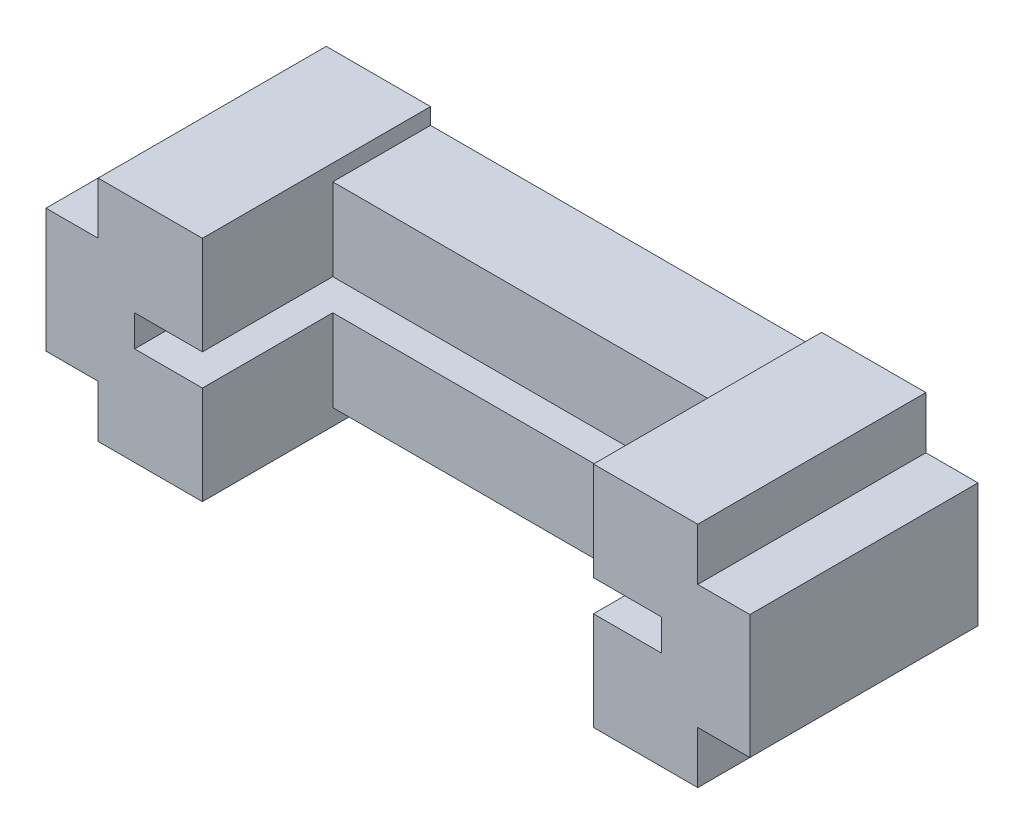
SolidWorks part; units mm, degrees
ref_plane "Front Plane" through (0, 0, 0) normal (0, 0, 1) x (1, 0, 0)
ref_plane "Top Plane" through (0, 0, 0) normal (0, 1, 0) x (1, 0, 0)
ref_plane "Right Plane" through (0, 0, 0) normal (1, 0, 0) x (0, 0, -1)
sketch "Sketch1" plane through (0, 0, 0) normal (0, 0, 1) x (1, 0, 0)
  line L1 (-29.21, -11.1125) -> (29.21, -11.1125)
  line L2 (-34.29, -6.0325) -> (-34.29, 6.0325)
  line L3 (-29.21, 11.1125) -> (29.21, 11.1125)
  line L4 (34.29, -6.0325) -> (34.29, 6.0325)
  line L9 (-34.29, 6.0325) -> (-29.21, 6.0325)
  line L10 (-29.21, 11.1125) -> (-29.21, 6.0325)
  line L13 (-34.29, -6.0325) -> (-29.21, -6.0325)
  line L14 (-29.21, -11.1125) -> (-29.21, -6.0325)
  line L17 (34.29, -6.0325) -> (29.21, -6.0325)
  line L18 (29.21, -11.1125) -> (29.21, -6.0325)
  line L21 (34.29, 6.0325) -> (29.21, 6.0325)
  line L22 (29.21, 11.1125) -> (29.21, 6.0325)
  point P0 (0, 0)
  point P2 (0, 11.1125)
  point P4 (-34.29, 0)
  dimension "D1" = 68.58
  dimension "D2" = 22.225
  dimension "D3" = 5.08
extrude "Boss-Extrude1" add sketch "Sketch1" along normal blind 9.525
sketch "Sketch3" plane through (0, 0, 9.525) normal (0, 0, 1) x (1, 0, 0)
  line L0 (29.21, 11.1125) -> (-29.21, 11.1125) construction
  line L1 (-29.21, 11.1125) -> (-19.05, 11.1125)
  line L2 (-34.29, 6.0325) -> (-34.29, -6.0325)
  line L3 (-29.21, -11.1125) -> (-19.05, -11.1125)
  line L4 (-19.05, 11.1125) -> (-19.05, 1.524)
  line L5 (-29.21, -11.1125) -> (29.21, -11.1125) construction
  line L6 (0, 0) -> (0, 11.1125) construction
  line L7 (-19.05, 1.524) -> (-25.654, 1.524)
  line L9 (-19.05, -1.524) -> (-25.654, -1.524)
  line L10 (-25.654, 1.524) -> (-25.654, -1.524)
  line L11 (-19.05, -1.524) -> (-19.05, -11.1125)
  line L12 (19.05, -1.524) -> (19.05, -11.1125)
  line L13 (25.654, 1.524) -> (25.654, -1.524)
  line L14 (19.05, -1.524) -> (25.654, -1.524)
  line L15 (19.05, 1.524) -> (25.654, 1.524)
  line L16 (19.05, 11.1125) -> (19.05, 1.524)
  line L17 (29.21, -11.1125) -> (19.05, -11.1125)
  line L18 (34.29, 6.0325) -> (34.29, -6.0325)
  line L19 (29.21, 11.1125) -> (19.05, 11.1125)
  line L20 (-34.29, 6.0325) -> (-34.29, -6.0325) construction
  line L21 (29.21, -11.1125) -> (29.21, -6.0325) construction
  line L24 (-34.29, 6.0325) -> (-29.21, 6.0325)
  line L25 (-29.21, 11.1125) -> (-29.21, 6.0325)
  line L26 (-29.21, -6.0325) -> (-34.29, -6.0325)
  line L27 (-29.21, -6.0325) -> (-29.21, -11.1125)
  line L32 (34.29, -6.0325) -> (29.21, -6.0325)
  line L33 (29.21, -11.1125) -> (29.21, -6.0325)
  line L34 (29.21, -6.0325) -> (34.29, -6.0325) construction
  line L37 (34.29, 6.0325) -> (29.21, 6.0325)
  line L38 (29.21, 11.1125) -> (29.21, 6.0325)
  line L39 (34.29, -6.0325) -> (34.29, 6.0325) construction
  point P12 (-25.654, 0)
  dimension "D1" = 6.604
  dimension "D2" = 3.048
  dimension "D4" = 19.05
extrude "Boss-Extrude2" add sketch "Sketch3" along normal blind 12.7
sketch "Sketch4" plane through (0, 0, 9.525) normal (0, 0, 1) x (1, 0, 0)
  line L1 (-25.654, -1.524) -> (25.654, -1.524)
  line L2 (-25.654, -1.524) -> (-25.654, 1.524)
  line L3 (-25.654, 1.524) -> (25.654, 1.524)
  line L4 (25.654, -1.524) -> (25.654, 1.524)
extrude "Cut-Extrude1" cut sketch "Sketch4" against normal blind 6.096
sketch "Sketch5" plane through (0, 0, 9.525) normal (0, 0, 1) x (1, 0, 0)
  line L0 (19.05, 11.1125) -> (-19.05, 11.1125) construction
  line L1 (-19.05, 11.1125) -> (19.05, 11.1125)
  line L2 (-19.05, 11.1125) -> (-19.05, 9.525)
  line L3 (-19.05, 9.525) -> (19.05, 9.525)
  line L4 (19.05, 11.1125) -> (19.05, 9.525)
  line L5 (0, 0) -> (12.7, 0) construction
  line L6 (19.05, -11.1125) -> (19.05, -9.525)
  line L7 (-19.05, -9.525) -> (19.05, -9.525)
  line L8 (-19.05, -11.1125) -> (-19.05, -9.525)
  line L9 (-19.05, -11.1125) -> (19.05, -11.1125)
  line L10 (-19.05, 1.524) -> (-19.05, 11.1125) construction
  point P6 (0, 9.525)
  dimension "D1" = 1.5875
extrude "Cut-Extrude2" cut sketch "Sketch5" against normal through all both and the other way through all
